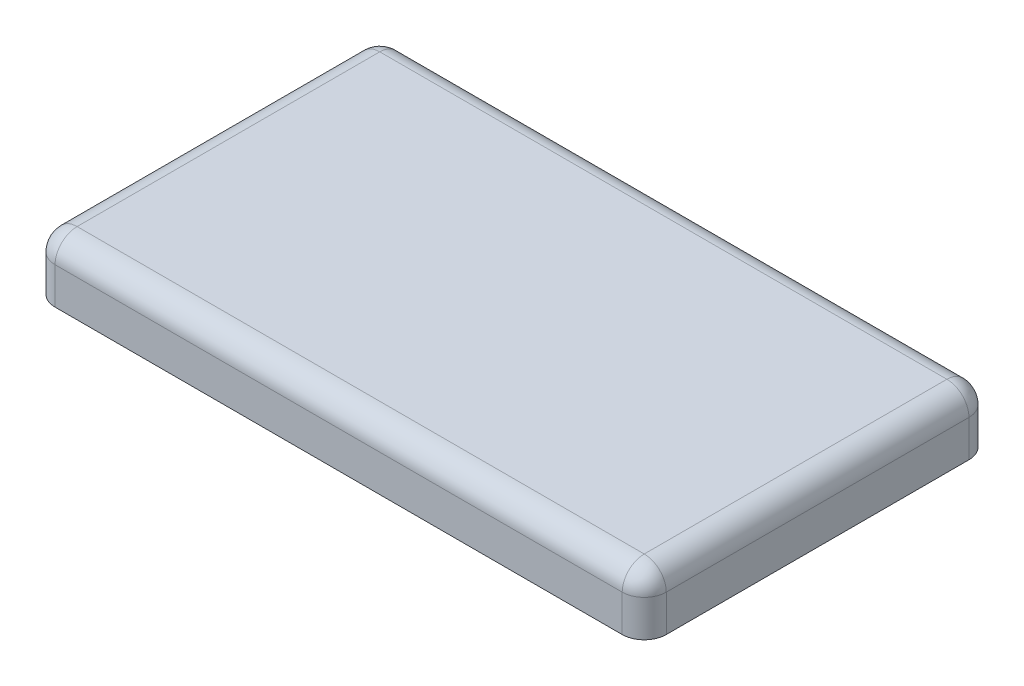
SolidWorks part; units mm, degrees
ref_plane "Front Plane" through (0, 0, 0) normal (0, 0, 1) x (1, 0, 0)
ref_plane "Top Plane" through (0, 0, 0) normal (0, 1, 0) x (1, 0, 0)
ref_plane "Right Plane" through (0, 0, 0) normal (1, 0, 0) x (0, 0, -1)
sketch "Sketch1" plane through (0, 0, 0) normal (0, 1, 0) x (1, 0, 0)
  line L1 (0, 0) -> (41.6, 0)
  line L2 (0, 0) -> (0, 23.6)
  line L3 (0, 23.6) -> (41.6, 23.6)
  line L4 (41.6, 0) -> (41.6, 23.6)
  dimension "D1" = 41.6
  dimension "D2" = 23.6
extrude "Boss-Extrude1" add sketch "Sketch1" along normal blind 4
sketch "Sketch2" plane through (0, 0, 0) normal (0, -1, 0) x (1, 0, 0)
  line L0 (20.8, 0) -> (20.8, -23.6) construction
  line L1 (0, 0) -> (41.6, 0) construction
  line L2 (41.6, -23.6) -> (0, -23.6) construction
  line L4 (1.55, -22.05) -> (40.05, -22.05)
  line L5 (1.55, -22.05) -> (1.55, -1.55)
  line L6 (1.55, -1.55) -> (40.05, -1.55)
  line L7 (40.05, -22.05) -> (40.05, -1.55)
  line L8 (1.55, -22.05) -> (40.05, -1.55) construction
  line L9 (1.55, -1.55) -> (40.05, -22.05) construction
  line L10 (0, -23.6) -> (41.6, -23.6) construction
  line L11 (0, -23.6) -> (0, 0) construction
  line L12 (0, 0) -> (41.6, 0) construction
  line L13 (41.6, -23.6) -> (41.6, 0) construction
  line L14 (0, -23.6) -> (41.6, 0) construction
  line L15 (0, 0) -> (41.6, -23.6) construction
  point P6 (20.8, -11.8)
  point P11 (20.8, -11.8)
  dimension "D1" = 1.55
  dimension "D2" = 1.55
extrude "Cut-Extrude1" cut sketch "Sketch2" against normal blind 2.6
fillet "Fillet1" radius 1.5 8 edges at (20.8, 4, -23.6) (41.6, 4, -11.8) (20.8, 4, 0) (0, 4, -11.8) (0, 2, 0) (0, 2, -23.6) (41.6, 2, -23.6) (41.6, 2, 0)
